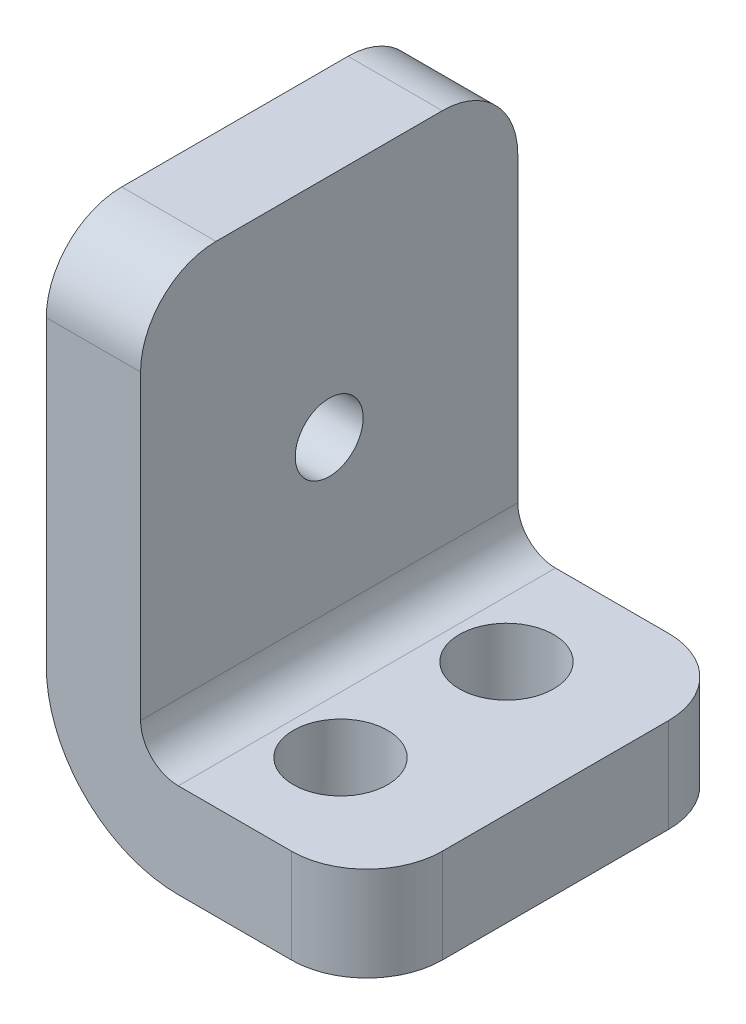
SolidWorks part; units mm, degrees
ref_plane "Front Plane" through (0, 0, 0) normal (0, 0, 1) x (1, 0, 0)
ref_plane "Top Plane" through (0, 0, 0) normal (0, 1, 0) x (1, 0, 0)
ref_plane "Right Plane" through (0, 0, 0) normal (1, 0, 0) x (0, 0, -1)
sketch "Sketch1" plane through (0, 0, 0) normal (0, 0, 1) x (1, 0, 0)
  line L0 (0, 25.6908) -> (0, 12.9908)
  line L1 (1.27, 11.7208) -> (7.62, 11.7208)
  line L2 (-3.175, 25.6908) -> (-3.175, 12.9908)
  line L3 (1.27, 8.5458) -> (7.62, 8.5458)
  line L4 (-3.175, 25.6908) -> (0, 25.6908)
  line L5 (7.62, 11.7208) -> (7.62, 8.5458)
  arc A0 (1.27, 11.7208) -> (0, 12.9908) centre (1.27, 12.9908) cw
  arc A1 (1.27, 8.5458) -> (-3.175, 12.9908) centre (1.27, 12.9908) cw
  dimension "D1" = 1.27
  dimension "D2" = 6.35
  dimension "D3" = 12.7
  dimension "D4" = 3.175
extrude "Boss-Extrude1" add sketch "Sketch1" along normal blind 12.7
fillet "Fillet1" radius 2.54 4 edges at (7.62, 10.1333, 12.7) (7.62, 10.1333, 0) (-1.5875, 25.6908, 12.7) (-1.5875, 25.6908, 0)
sketch "Sketch2" plane through (0, 0, 0) normal (1, 0, 0) x (0, 0, -1)
  line L0 (-10.16, 25.6908) -> (-2.54, 25.6908) construction
  line L1 (0, 23.1508) -> (0, 12.9908) construction
  circle A0 centre (-6.35, 18.0708) radius 1.143
  point P2 (-6.0312, 21.3874)
  point P3 (0, 0)
  point P6 (-6.35, 25.6908)
  point P7 (0, 0)
  point P10 (0, 18.0708)
  point P11 (-6.35, 18.0708)
  dimension "D1" = 2.286
extrude "Cut-Extrude1" cut sketch "Sketch2" against normal up to next (3.175 mm away) from surface at 0 starting at face at (0, 20.7861, 6.35)
sketch "Sketch3" plane through (0, 11.7208, 0) normal (0, 1, 0) x (1, 0, 0)
  line L0 (3.175, -12.7) -> (3.175, 0)
  line L1 (5.08, -12.7) -> (1.27, -12.7) construction
  line L2 (5.08, 0) -> (1.27, 0) construction
  circle A0 centre (3.175, -9.144) radius 1.5875
  circle A1 centre (3.175, -3.556) radius 1.5875
  point P10 (0, 0)
  dimension "D1" = 3.556
  dimension "D3" = 3.175
  dimension "D4" = 3.175
  dimension "D2" = 3.556
extrude "Cut-Extrude2" cut sketch "Sketch3" against normal up to next contours L0 A0 | L0 A0 | L0 A1 | L0 A1
sketch "Sketch4" plane through (0, 8.5458, 0) normal (0, -1, 0) x (1, 0, 0)
  line L0 (1.27, 6.35) -> (7.62, 6.35)
  line L1 (1.27, 12.7) -> (1.27, 0) construction
  line L2 (7.62, 10.16) -> (7.62, 2.54) construction
